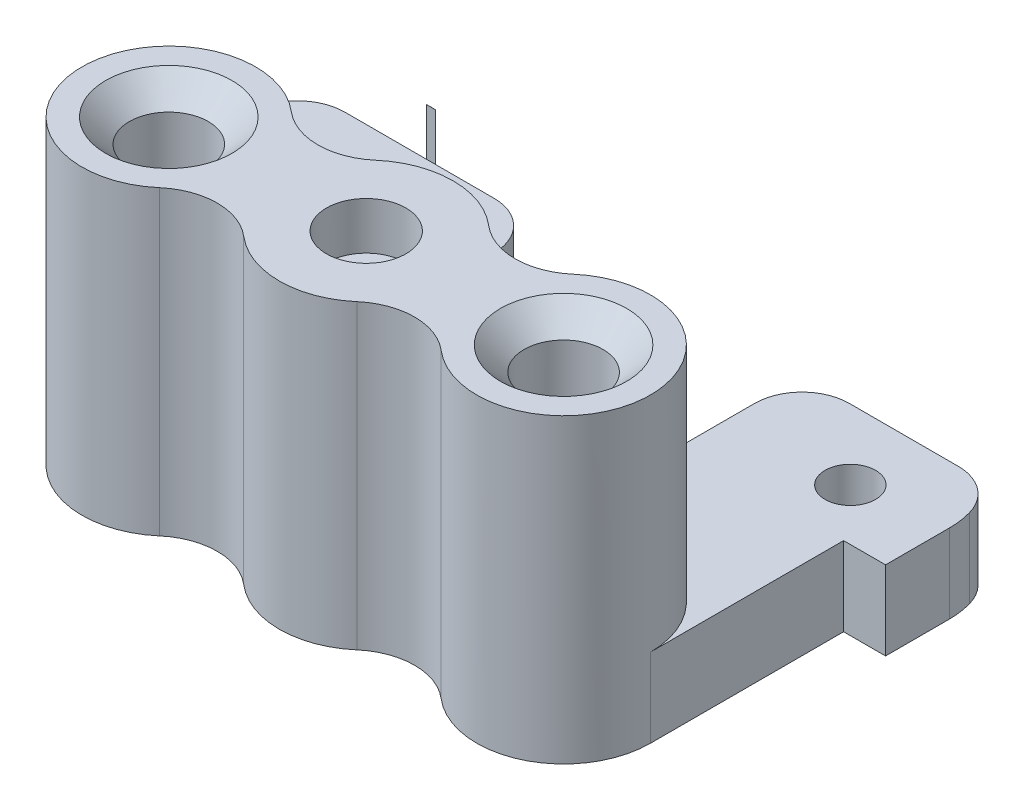
SolidWorks part; units mm, degrees
ref_plane "Front Plane" through (0, 0, 0) normal (0, 0, 1) x (1, 0, 0)
ref_plane "Top Plane" through (0, 0, 0) normal (0, 1, 0) x (1, 0, 0)
ref_plane "Right Plane" through (0, 0, 0) normal (1, 0, 0) x (0, 0, -1)
ref_plane "Plane1" through (0, 0, 0) normal (0, -1, 0) x (1, 0, 0)
sketch "Sketch1" plane through (0, 0, 0) normal (0, -1, 0) x (1, 0, 0)
  line L0 (9.5, 3.2686) -> (19.8429, 3.2686)
  line L1 (19.8429, 3.2686) -> (19.8429, 15.5)
  line L2 (-15.8261, 17.3793) -> (-22.169, -0.0664)
  line L3 (-16.7151, -7.4384) -> (-7, -7.4384)
  line L4 (-7, -7.4384) -> (-7, 3.5521)
  line L5 (-8.3801, 7.3208) -> (-5.5488, 15.5)
  line L6 (-5.5488, 15.5) -> (11.5, 15.5)
  line L7 (11.5, 15.5) -> (11.5, 6.7327)
  line L8 (-10.6571, 15.5) -> (14.3429, 15.5) construction
  line L9 (-24, 9) -> (30, 9) construction
  arc A0 (19.8429, 15.5) -> (10.7621, 19.6747) centre (14.3429, 15.5) ccw
  arc A1 (10.7621, 19.6747) -> (5.4236, 19.6747) centre (8.0929, 22.7868) cw
  arc A2 (5.4236, 19.6747) -> (-1.7379, 19.6747) centre (1.8429, 15.5) ccw
  arc A3 (-1.7379, 19.6747) -> (-7.0764, 19.6747) centre (-4.4071, 22.7868) cw
  arc A4 (-7.0764, 19.6747) -> (-15.8261, 17.3793) centre (-10.6571, 15.5) ccw
  arc A5 (-22.169, -0.0664) -> (-16.7151, -7.4384) centre (-17, -1.9458) ccw
  arc A6 (-7, 3.5521) -> (-7.745, 5.1093) centre (-9, 3.5521) ccw
  arc A7 (-7.745, 5.1093) -> (-8.3801, 7.3208) centre (-6.4901, 6.6666) cw
  arc A8 (11.5, 6.7327) -> (10.5, 5.0006) centre (9.5, 6.7327) cw
  arc A9 (10.5, 5.0006) -> (9.5, 3.2686) centre (11.5, 3.2686) ccw
  dimension "D1" = 5.5
  dimension "D2" = 4.1
  dimension "D3" = 5.5
  dimension "D4" = 4.1
  dimension "D5" = 5.5
  dimension "D6" = 6.5
  dimension "D7" = 25
extrude "Boss-Extrude1" add sketch "Sketch1" against normal blind 5
sketch "Sketch2" plane through (0, 5, 0) normal (0, 1, 0) x (-1, 0, 0)
  arc A0 (7.0764, 11.3253) -> (1.7379, 11.3253) centre (4.4071, 8.2132) ccw
  arc A1 (1.7379, 11.3253) -> (-5.4236, 11.3253) centre (-1.8429, 15.5) cw
  arc A2 (-5.4236, 11.3253) -> (-10.7621, 11.3253) centre (-8.0929, 8.2132) ccw
  arc A3 (-10.7621, 11.3253) -> (-10.7621, 19.6747) centre (-14.3429, 15.5) cw
  arc A4 (-10.7621, 19.6747) -> (-5.4236, 19.6747) centre (-8.0929, 22.7868) ccw
  arc A5 (-5.4236, 19.6747) -> (1.7379, 19.6747) centre (-1.8429, 15.5) cw
  arc A6 (1.7379, 19.6747) -> (7.0764, 19.6747) centre (4.4071, 22.7868) ccw
  arc A7 (7.0764, 19.6747) -> (7.0764, 11.3253) centre (10.6571, 15.5) cw
  arc A9 (1.7379, 19.6747) -> (7.0764, 19.6747) centre (4.4071, 22.7868) ccw construction
  arc A10 (-10.7621, 19.6747) -> (-5.4236, 19.6747) centre (-8.0929, 22.7868) ccw construction
  arc A11 (15.8261, 17.3793) -> (7.0764, 19.6747) centre (10.6571, 15.5) ccw construction
  arc A12 (-10.7621, 19.6747) -> (-19.8429, 15.5) centre (-14.3429, 15.5) ccw construction
  arc A13 (1.7379, 19.6747) -> (-5.4236, 19.6747) centre (-1.8429, 15.5) ccw construction
extrude "Boss-Extrude2" add sketch "Sketch2" along normal offset from surface 1.5 and the other way up to surface
sketch "Sketch3" plane through (0, 0, 3.2686) normal (0, 0, -1) x (-1, 0, 0)
  line L0 (-9.5, 0) -> (-22.5, 0)
  line L1 (-22.5, 0) -> (-22.5, 5)
  line L2 (-22.5, 5) -> (-9.5, 5)
  line L3 (-9.5, 5) -> (-9.5, 0)
extrude "Boss-Extrude3" add sketch "Sketch3" along normal blind 9.5359
sketch "Sketch4" plane through (0, 19.1, 0) normal (0, 1, 0) x (-1, 0, 0)
  circle A0 centre (-17, 26) radius 5.5
sketch "Sketch5" plane through (0, 19.1, 0) normal (0, 1, 0) x (-1, 0, 0)
  circle A0 centre (8, 26) radius 5.5
hole_wizard "CBORE for M3 Hex Head Machine Screw1" positions "Sketch7" profile "Sketch6" counterbore size "M3" standard "ANSI Metric"
sketch "Sketch7" plane through (0, 0, 0) normal (0, -1, 0) x (-1, 0, 0)
  point P0 (17, 0)
  point P1 (-17, 0)
sketch "Sketch6" plane through (-17, 0, 0) normal (1, 0, 0) x (0, 0, -1)
  line L0 (0, 0) -> (0, 19.1)
  line L1 (0, 19.1) -> (1.6, 19.1)
  line L3 (1.6, 19.1) -> (1.6, 3)
  line L4 (1.6, 3) -> (3.5, 3)
  line L5 (3.5, 3) -> (3.5, 0)
  line L7 (3.5, 0) -> (0, 0)
  line L11 (0, -6.35) -> (0, 107.95) construction
  dimension "Thru Hole Dia." = 3.2
  dimension "Thru Hole Depth" = 19.1
  dimension "C'Bore Dia." = 7
  dimension "C'Bore Depth" = 3
hole_wizard "Hole1" positions "Sketch9" profile "Sketch8" legacy end condition through all
sketch "Sketch9" plane through (0, 0, 0) normal (0, -1, 0) x (-1, 0, 0)
  point P4 (-1.8429, -15.5)
sketch "Sketch8" plane through (1.8429, 0, 15.5) normal (1, 0, 0) x (0, 0, -1)
  line L0 (0, 0) -> (0, 19.1)
  line L1 (0, 19.1) -> (2.5175, 19.1)
  line L2 (2.5175, 19.1) -> (2.5175, 0)
  line L3 (2.5175, 0) -> (0, 0)
  line L4 (0, 110) -> (0, -10) construction
  dimension "Diameter" = 5.035
  dimension "Depth" = 19.1
hole_wizard "Ø5.0 (5) Diameter Hole1" positions "Sketch11" profile "Sketch10" hole size "Ø5.0" standard "ANSI Metric" end condition through all
sketch "Sketch11" plane through (0, 0, 0) normal (0, -1, 0) x (-1, 0, 0)
  point P0 (10.6571, -15.5)
  point P1 (-14.3429, -15.5)
  point P2 (10.6571, -15.5)
sketch "Sketch10" plane through (-10.6571, 0, 15.5) normal (1, 0, 0) x (0, 0, -1)
  line L0 (0, 0) -> (0, 19.1)
  line L1 (0, 19.1) -> (2.5, 19.1)
  line L2 (2.5, 19.1) -> (2.5, 0)
  line L5 (2.5, 0) -> (0, 0)
  line L11 (0, -6.35) -> (0, 107.95) construction
  dimension "Thru Hole Dia." = 5
  dimension "Thru Hole Depth" = 19.1
ref_plane "Plane2" through (-15.181, 0, 5.255) normal (-0.945, 0, 0.3271) x (0, -1, 0)
sketch "Sketch12" plane through (-15.181, 0, 5.255) normal (-0.945, 0, 0.3271) x (0, -1, 0)
  line L0 (-19.1, 5.6612) -> (-19.1, 14.9528)
  line L1 (-19.1, 14.9528) -> (-5, -6.8388)
  line L2 (-19.1, 16.6612) -> (-19.1, 5.6612) construction
  line L3 (-5, 11.2463) -> (-5, -7.3145) construction
  line L5 (-19.1, 5.6612) -> (-5, 5.6612) construction
  dimension "D1" = 12.5
ref_plane "Plane3" through (17.0104, 0, 0) normal (-1, 0, 0) x (0, -1, 0)
sketch "Sketch13" plane through (17.0104, 0, 0) normal (-1, 0, 0) x (0, -1, 0)
  line L0 (-19.1, 10) -> (-19.1, 19)
  line L1 (-19.1, 19) -> (-5, 10)
  line L2 (-19.1, 21) -> (-19.1, 10) construction
  line L3 (-19.1, 10) -> (-5, 10) construction
  line L4 (-5, 3.2686) -> (-5, 15.5) construction
  line L5 (-5, 9) -> (-6.6, 9) construction
  dimension "D1" = 1
chamfer "Chamfer1" distance 1.5 angle 45 2 edges at (14.3429, 19.1, 13) (-10.6571, 19.1, 13)
fillet "Fillet3" radius 5.5 1 edges at (22.5, 2.5, -6.2673)
sketch "Sketch14" plane through (0, 0, 0) normal (0, -1, 0) x (1, 0, 0)
  circle A2 centre (17, 0) radius 1.6
  circle A3 centre (17, 0) radius 3.5
  circle A6 centre (17, 0) radius 1.6 construction
  circle A7 centre (17, 0) radius 3.5 construction
  circle A8 centre (-17, 0) radius 3.5
  circle A9 centre (-17, 0) radius 1.6
  circle A10 centre (-17, 0) radius 1.6 construction
  circle A11 centre (-17, 0) radius 3.5 construction
extrude "Boss-Extrude6" add sketch "Sketch14" against normal up to surface (3 mm away) up to face at (-17, 3, -1.6)
sketch "Sketch16" plane through (0, 0, 0) normal (0, -1, 0) x (1, 0, 0)
  circle A2 centre (1.8429, 15.5) radius 2.5175
  circle A3 centre (1.8429, 15.5) radius 2.5175 construction
extrude "Boss-Extrude7" add sketch "Sketch16" against normal offset from surface (16.1 mm away) 3 up to face at (10.3429, 19.1, 15.5)
sketch "Sketch17" plane through (0, 0, 0) normal (0, -1, 0) x (1, 0, 0)
  line L0 (-16.7151, -7.4384) -> (-7, -7.4384) construction
  line L1 (-21.9027, -7.4384) -> (21.0955, -7.4384)
  line L2 (-21.9027, -7.4384) -> (-21.9027, -4.4384)
  line L3 (-21.9027, -4.4384) -> (21.0955, -4.4384)
  line L4 (21.0955, -7.4384) -> (21.0955, -4.4384)
  arc A0 (-22.169, -0.0664) -> (-16.7151, -7.4384) centre (-17, -1.9458) ccw construction
  arc A1 (17, -6.2673) -> (22.5, -0.7673) centre (17, -0.7673) ccw construction
  dimension "D1" = 3
extrude "Cut-Extrude1" cut sketch "Sketch17" against normal through all
fillet "Fillet4" radius 3 4 edges at (21.0955, 2.5, -4.4384) (9.5, 2.5, -4.4384) (-7, 2.5, -4.4384) (-21.9027, 2.5, -4.4384)
